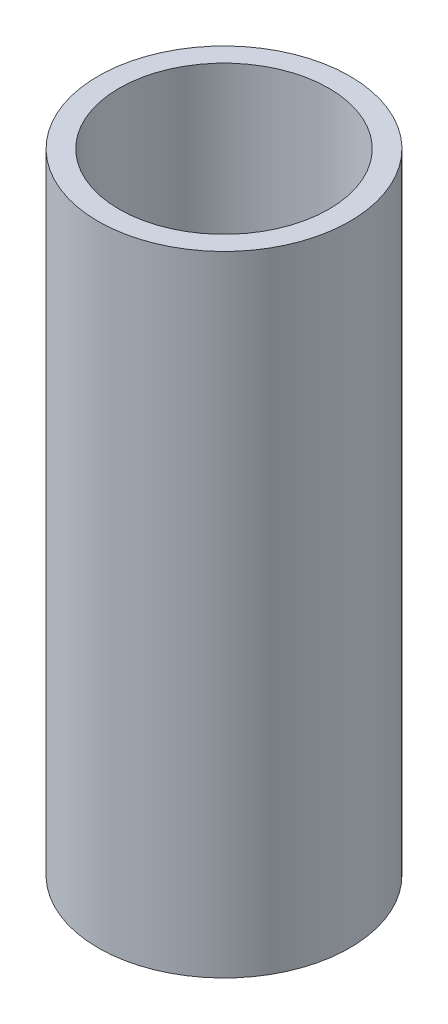
SolidWorks part; units mm, degrees
ref_plane "Front Plane" through (0, 0, 0) normal (0, 0, 1) x (1, 0, 0)
ref_plane "Top Plane" through (0, 0, 0) normal (0, 1, 0) x (1, 0, 0)
ref_plane "Right Plane" through (0, 0, 0) normal (1, 0, 0) x (0, 0, -1)
sketch "Sketch1" plane through (0, 0, 0) normal (0, 1, 0) x (1, 0, 0)
  circle A0 centre (0, 0) radius 12
  circle A1 centre (0, 0) radius 10
  dimension "D1" = 24
  dimension "D2" = 20
extrude "Boss-Extrude1" add sketch "Sketch1" along normal blind 60
